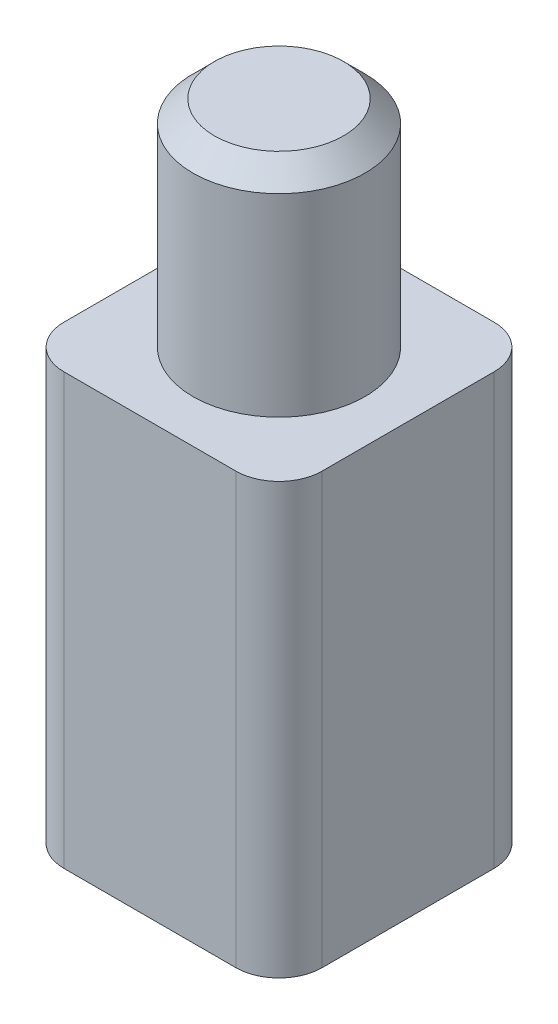
SolidWorks part; units mm, degrees
ref_plane "Front Plane" through (0, 0, 0) normal (0, 0, 1) x (1, 0, 0)
ref_plane "Top Plane" through (0, 0, 0) normal (0, 1, 0) x (1, 0, 0)
ref_plane "Right Plane" through (0, 0, 0) normal (1, 0, 0) x (0, 0, -1)
sketch "Sketch1" plane through (0, 0, 0) normal (0, 1, 0) x (1, 0, 0)
  line L1 (-30, -30) -> (30, -30)
  line L2 (-30, -30) -> (-30, 30)
  line L3 (-30, 30) -> (30, 30)
  line L4 (30, -30) -> (30, 30)
  line L5 (-30, -30) -> (30, 30) construction
  line L6 (-30, 30) -> (30, -30) construction
  point P0 (0, 0)
  dimension "D1" = 60
  dimension "D2" = 60
extrude "Boss-Extrude1" add sketch "Sketch1" along normal blind 100 contours L2 L1 L4 L3
sketch "Sketch2" plane through (0, 100, 0) normal (0, 1, 0) x (1, 0, 0)
  circle A0 centre (0, 0) radius 20
  dimension "D1" = 40
extrude "Boss-Extrude2" add sketch "Sketch2" along normal blind 50
sketch "Sketch3" plane through (0, 0, 0) normal (0, -1, 0) x (1, 0, 0)
  line L1 (-15.219, 16.1911) -> (14.781, 16.1911)
  line L2 (-15.219, 16.1911) -> (-15.219, -13.8089)
  line L3 (-15.219, -13.8089) -> (14.781, -13.8089)
  line L4 (14.781, 16.1911) -> (14.781, -13.8089)
  dimension "D1" = 30
  dimension "D2" = 30
extrude "Cut-Extrude1" cut sketch "Sketch3" against normal blind 30
sketch "Sketch6" plane through (0, 30, 0) normal (0, -1, 0) x (1, 0, 0)
  circle A0 centre (0, 0) radius 12.5
  dimension "D1" = 25
extrude "Cut-Extrude7" cut sketch "Sketch6" against normal blind 40
fillet "Fillet1" radius 10 4 edges at (30, 50, -30) (-30, 50, -30) (30, 50, 30) (-30, 50, 30)
fillet "Fillet2" radius 10 4 edges at (14.781, 15, 16.1911) (-15.219, 15, 16.1911) (14.781, 15, -13.8089) (-15.219, 15, -13.8089)
chamfer "Chamfer1" distance 5 angle 45 1 edges at (0, 150, 20)
chamfer "Chamfer2" distance 5 angle 30 1 edges at (0, 70, -12.5)
